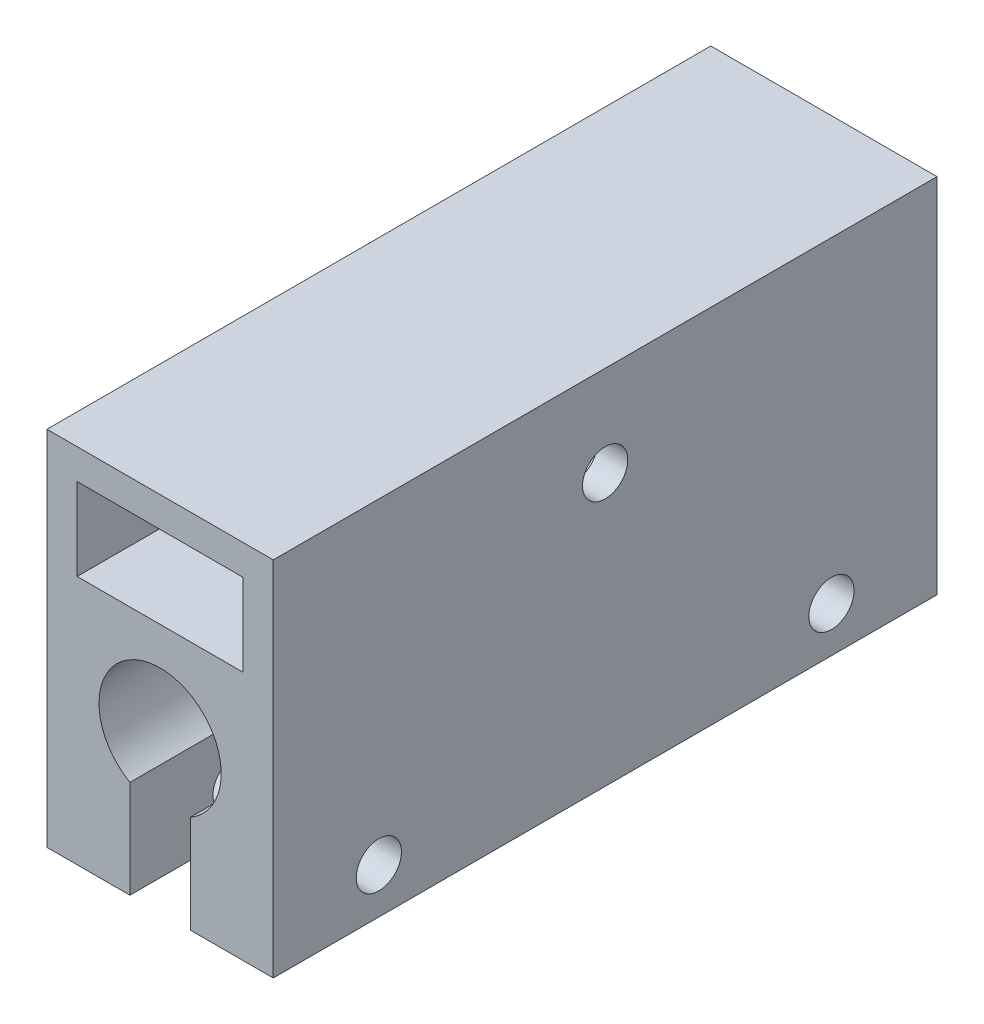
SolidWorks part; units mm, degrees
material "POM 乙缩醛共聚物"
ref_plane "前视基准面" through (0, 0, 0) normal (0, 0, 1) x (1, 0, 0)
ref_plane "上视基准面" through (0, 0, 0) normal (0, 1, 0) x (1, 0, 0)
ref_plane "右视基准面" through (0, 0, 0) normal (1, 0, 0) x (0, 0, -1)
sketch "草图1" plane through (0, 0, 0) normal (0, 0, 1) x (1, 0, 0)
  line L0 (0, 31.745) -> (0, -32.7841) construction
  line L1 (-39.1747, 0) -> (38.9669, 0) construction
  line L2 (2, -10) -> (7.5, -10)
  line L3 (-7.5, 14) -> (7.5, 14)
  line L4 (-7.5, 14) -> (-7.5, -10)
  line L5 (-7.5, -10) -> (-2, -10)
  line L6 (7.5, 14) -> (7.5, -10)
  line L7 (-5.5, 12) -> (5.5, 12)
  line L8 (-5.5, 12) -> (-5.5, 6.55)
  line L9 (-5.5, 6.55) -> (5.5, 6.55)
  line L10 (5.5, 12) -> (5.5, 6.55)
  line L11 (-5.5, 12) -> (5.5, 6.55) construction
  line L12 (-5.5, 6.55) -> (5.5, 12) construction
  line L14 (-2, -3.5217) -> (-2, -10)
  line L16 (2, -3.5217) -> (2, -10)
  arc A0 (2, -3.5217) -> (-2, -3.5217) centre (0, 0) ccw
  point P11 (0, 9.275)
  dimension "D1" = 8.1
  dimension "D2" = 10
  dimension "D3" = 14
  dimension "D4" = 15
  dimension "D5" = 2
  dimension "D6" = 2
  dimension "D7" = 2.5
  dimension "D8" = 4
extrude "凸台-拉伸1" add sketch "草图1" along normal blind 44
sketch "草图2" plane through (0, 14, 0) normal (0, 1, 0) x (1, 0, 0)
  line L0 (0, 0) -> (0, -44) construction
  line L1 (7.5, -44) -> (-7.5, -44) construction
  line L2 (-7.5, -22) -> (10.7243, -22) construction
  line L3 (-7.5, -44) -> (-7.5, 0) construction
  circle A0 centre (0, -7) radius 2
  circle A1 centre (0, -37) radius 2
  dimension "D1" = 4
  dimension "D2" = 30
extrude "切除-拉伸1" [suppressed] cut sketch "草图2" against normal up to surface (2 mm away)
sketch "草图3" plane through (-7.5, 0, 0) normal (-1, 0, 0) x (0, 0, 1)
  line L0 (22, -10) -> (22, 26) construction
  line L1 (44, -10) -> (0, -10) construction
  line L2 (0, -7) -> (44, -7) construction
  line L3 (0, 14) -> (0, -10) construction
  line L4 (44, 14) -> (44, -10) construction
  circle A0 centre (7, -7) radius 1.5
  circle A1 centre (37, -7) radius 1.5
  circle A2 centre (22, 8) radius 1.5
  dimension "D1" = 3
  dimension "D2" = 30
  dimension "D4" = 3
  dimension "D5" = 15
  dimension "D3" = 3
extrude "切除-拉伸2" cut sketch "草图3" against normal through all
